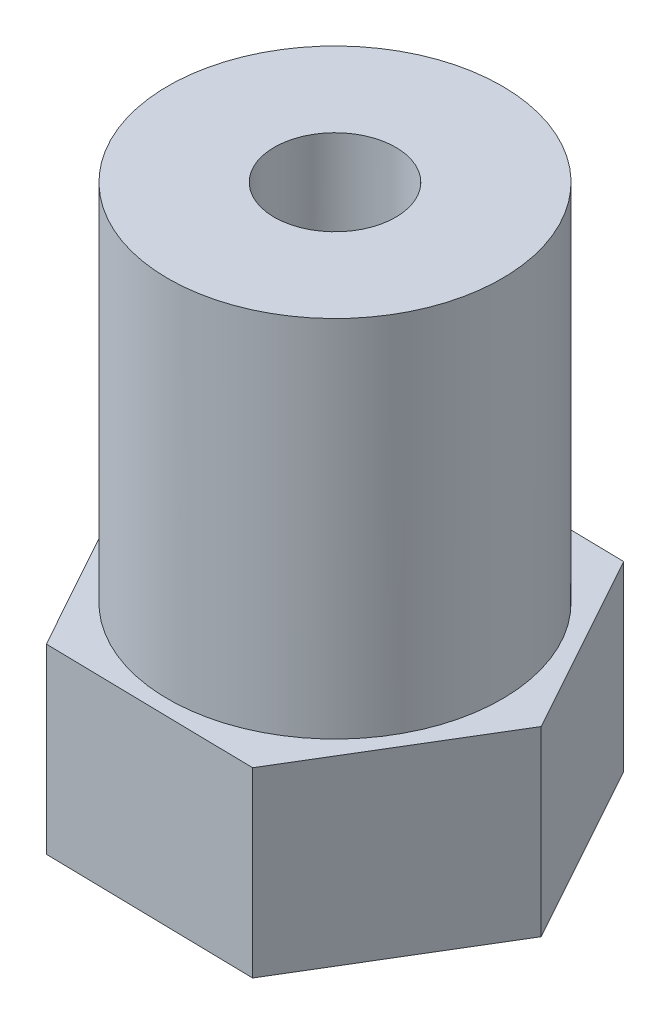
SolidWorks part; units mm, degrees
material "黄铜"
ref_plane "前视基准面" through (0, 0, 0) normal (0, 0, 1) x (1, 0, 0)
ref_plane "上视基准面" through (0, 0, 0) normal (0, 1, 0) x (1, 0, 0)
ref_plane "右视基准面" through (0, 0, 0) normal (1, 0, 0) x (0, 0, -1)
sketch "草图1" plane through (0, 0, 0) normal (0, 1, 0) x (1, 0, 0)
  circle A0 centre (0, 0) radius 5.5
  dimension "D1" = 11
extrude "凸台-拉伸1" add sketch "草图1" along normal blind 12
sketch "草图2" plane through (0, 12, 0) normal (0, 1, 0) x (1, 0, 0)
  circle A0 centre (0, 0) radius 2
  dimension "D1" = 4
extrude "切除-拉伸1" cut sketch "草图2" against normal blind 12
ref_plane "基准面2" through (0, 0, 0) normal (0, -1, 0) x (-1, 0, 0)
sketch "草图3" plane through (0, 0, 0) normal (0, -1, 0) x (-1, 0, 0)
  line L1 (3.578, -5.9328) -> (6.9269, 0.1322)
  line L2 (6.9269, 0.1322) -> (3.349, 6.065)
  line L3 (3.349, 6.065) -> (-3.578, 5.9328)
  line L4 (-3.578, 5.9328) -> (-6.9269, -0.1322)
  line L5 (-6.9269, -0.1322) -> (-3.349, -6.065)
  line L6 (-3.349, -6.065) -> (3.578, -5.9328)
  circle A0 centre (0, 0) radius 6 construction
  dimension "D1" = 12
  dimension "D2" = 6
extrude "凸台-拉伸2" add sketch "草图3" along normal blind 6
sketch "草图4" plane through (0, -6, 0) normal (0, -1, 0) x (1, 0, 0)
  circle A0 centre (0, 0) radius 2
  dimension "D1" = 4
extrude "切除-拉伸2" cut sketch "草图4" against normal through all
ref_plane "基准面3" through (0.1145, 0, -5.9989) normal (0.0191, 0, -0.9998) x (-0.9998, 0, -0.0191)
sketch "草图5" plane through (0.1145, 0, -5.9989) normal (0.0191, 0, -0.9998) x (-0.9998, 0, -0.0191)
  line L0 (0, -6) -> (0, 18.0376) construction
  line L1 (3.4641, -6) -> (-3.4641, -6) construction
  line L2 (0, 18.0376) -> (0, -15.9409) construction
  line L3 (-55, 0) -> (55, 0) construction
  circle A0 centre (0, 6) radius 2
  dimension "D1" = 4
  dimension "D2" = 6
extrude "切除-拉伸3" cut sketch "草图5" against normal blind 6
